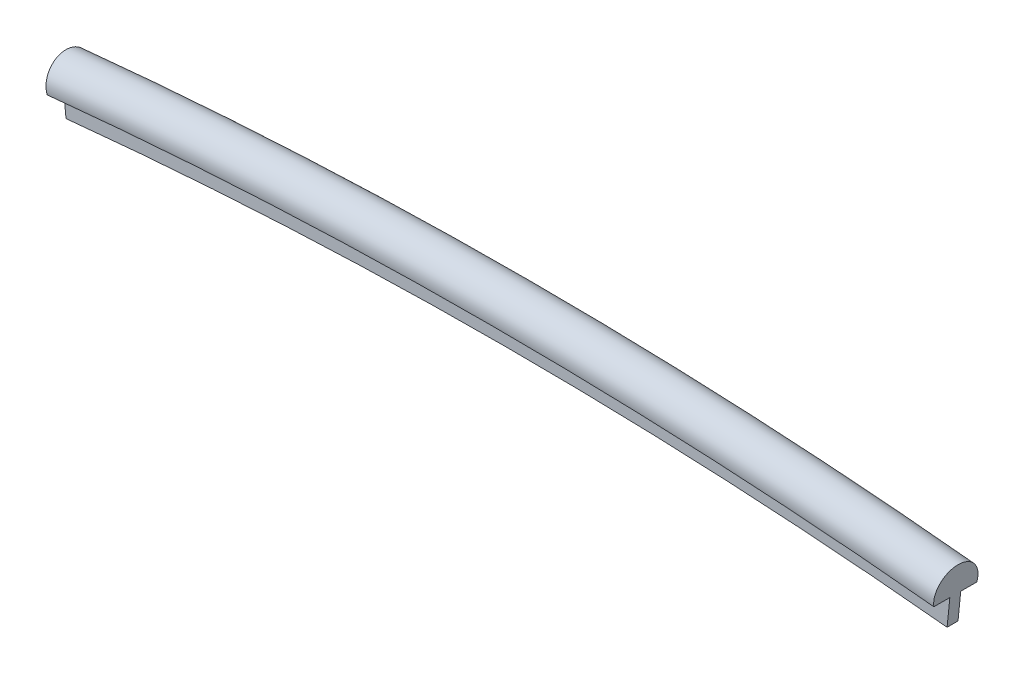
SolidWorks part; units mm, degrees
ref_plane "Front Plane" through (0, 0, 0) normal (0, 0, 1) x (1, 0, 0)
ref_plane "Top Plane" through (0, 0, 0) normal (0, 1, 0) x (1, 0, 0)
ref_plane "Right Plane" through (0, 0, 0) normal (1, 0, 0) x (0, 0, -1)
sketch "Sketch2" plane through (0, 0, 0) normal (1, 0, 0) x (0, 0, -1)
  line L0 (0, 241.3) -> (0, 0) construction
  line L2 (0, 241.3) -> (0, 239.8) construction
  line L3 (0, 239.8) -> (0.3, 239.8)
  line L4 (0, 239.8) -> (-0.3, 239.8)
  line L5 (-0.3, 239.8) -> (-0.3, 241.3)
  line L6 (0.3, 239.8) -> (0.3, 241.3)
  line L7 (0, 241.3) -> (0, 242.8) construction
  line L8 (-1.18, 241.3) -> (-0.3, 241.3)
  line L9 (0.3, 241.3) -> (1.18, 241.3)
  arc A0 (-1.18, 241.3) -> (1.18, 241.3) centre (0, 241.586) cw
  point P14 (0, 241.3)
ref_axis "Axis2" through (0, 0, 70.5976) along (0, 0, -1)
revolve "Revolve1" add sketch "Sketch2" angle 5.8 about axis through (0, 0, 70.5976) along (0, 0, -1)
